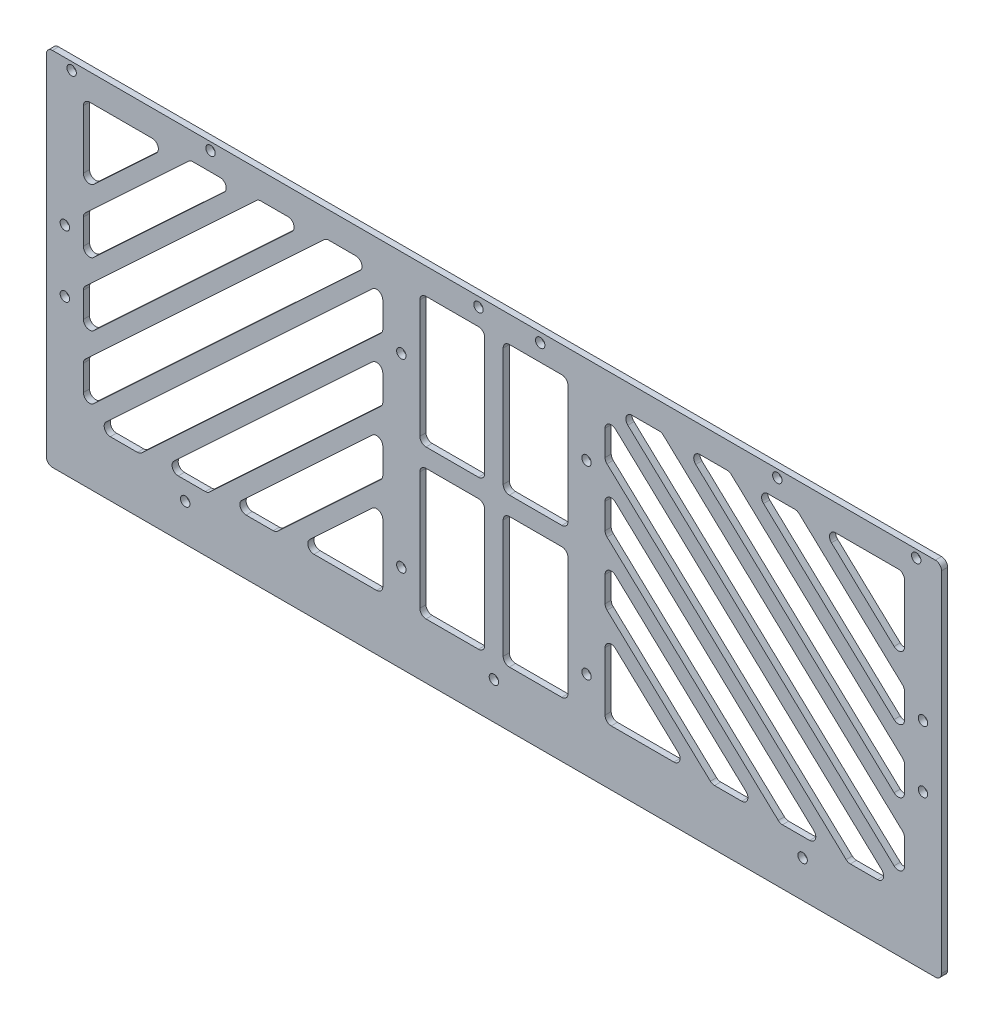
SolidWorks part; units mm, degrees
material "Thornel Mat VMA"
ref_plane "前视基准面" through (0, 0, 0) normal (0, 0, 1) x (1, 0, 0)
ref_plane "上视基准面" through (0, 0, 0) normal (0, 1, 0) x (1, 0, 0)
ref_plane "右视基准面" through (0, 0, 0) normal (1, 0, 0) x (0, 0, -1)
sketch "草图1" plane through (0, 0, 0) normal (0, 0, 1) x (1, 0, 0)
  line L1 (-145, -58.5) -> (145, -58.5)
  line L2 (-145, -58.5) -> (-145, 58.5)
  line L3 (-145, 58.5) -> (145, 58.5)
  line L4 (145, -58.5) -> (145, 58.5)
  line L5 (0, 58.5) -> (0, -58.5) construction
  line L6 (-145, 0) -> (145, 0) construction
  point P0 (0, 0)
  dimension "D1" = 290
  dimension "D2" = 117
extrude "凸台-拉伸1" add sketch "草图1" along normal mid plane 2
sketch "草图2" plane through (0, 0, 1) normal (0, 0, 1) x (1, 0, 0)
  circle A0 centre (136.8, 56) radius 1.25 construction
  circle A1 centre (91.8, 56) radius 1.25 construction
  circle A2 centre (136.8, 56) radius 1.25 construction
  circle A3 centre (91.8, 56) radius 1.25 construction
  circle A4 centre (91.8, 56) radius 1.525
  circle A5 centre (136.8, 56) radius 1.525
  dimension "D1" = 3.05
extrude "切除-拉伸1" cut sketch "草图2" against normal blind 10
mirror "镜向1" about plane through (0, 0, 0) normal (1, 0, 0) of "切除-拉伸1"
sketch "草图3" plane through (0, 0, 1) normal (0, 0, 1) x (1, 0, 0)
  line L0 (-100, -46.5) -> (100, -46.5) construction
  line L1 (0, 0) -> (0, -46.5) construction
  line L2 (-145, -58.5) -> (145, -58.5) construction
  circle A0 centre (-100, -46.5) radius 1.525
  circle A1 centre (0, -46.5) radius 1.525
  circle A2 centre (100, -46.5) radius 1.525
  point P3 (0, -46.5)
  dimension "D3" = 3.05
  dimension "D1" = 12
  dimension "D2" = 200
extrude "切除-拉伸2" cut sketch "草图3" against normal blind 10
sketch "草图4" plane through (0, 0, 1) normal (0, 0, 1) x (1, 0, 0)
  line L0 (0, 0) -> (0, 58.5) construction
  line L1 (145, 58.5) -> (-145, 58.5) construction
  circle A0 centre (-139, -8.5) radius 1.25 construction
  circle A1 centre (-139, 11.5) radius 1.25 construction
  circle A2 centre (-139, -8.5) radius 1.25 construction
  circle A3 centre (-139, 11.5) radius 1.25 construction
  circle A6 centre (-139, 11.5) radius 1.525
  circle A7 centre (-139, -8.5) radius 1.525
  dimension "D1" = 3.05
extrude "切除-拉伸3" cut sketch "草图4" against normal blind 10
mirror "镜向2" about plane through (0, 0, 0) normal (1, 0, 0) of "切除-拉伸3"
fillet "圆角1" radius 2 4 edges at (145, -58.5, 0) (-145, -58.5, 0) (-145, 58.5, 0) (145, 58.5, 0)
sketch "草图5" plane through (0, 0, 1) normal (0, 0, 1) x (1, 0, 0)
  circle A0 centre (15, 55.5) radius 1.25 construction
  circle A1 centre (-5, 55.5) radius 1.25 construction
  circle A2 centre (15, 55.5) radius 1.25 construction
  circle A3 centre (-5, 55.5) radius 1.25 construction
  circle A4 centre (-5, 55.5) radius 1.525
  circle A5 centre (15, 55.5) radius 1.525
  dimension "D1" = 3.05
extrude "切除-拉伸4" cut sketch "草图5" against normal blind 10
sketch "草图6" plane through (0, 0, 1) normal (0, 0, 1) x (1, 0, 0)
  line L1 (-30, -30) -> (30, -30) construction
  line L2 (-30, -30) -> (-30, 30) construction
  line L3 (-30, 30) -> (30, 30) construction
  line L4 (30, -30) -> (30, 30) construction
  line L5 (0, 30) -> (0, -30) construction
  line L6 (-30, 0) -> (30, 0) construction
  circle A0 centre (-30, 30) radius 1.525
  circle A1 centre (-30, -30) radius 1.525
  circle A2 centre (30, -30) radius 1.525
  circle A3 centre (30, 30) radius 1.525
  point P0 (0, 0)
  dimension "D3" = 3.05
  dimension "D1" = 60
  dimension "D2" = 60
extrude "切除-拉伸5" cut sketch "草图6" against normal blind 10
sketch "草图7" plane through (0, 0, 1) normal (0, 0, 1) x (1, 0, 0)
  line L0 (-36, 50) -> (-133, -40.5) construction
  line L1 (-133, 50) -> (-36, 50)
  line L2 (-133, 50) -> (-133, -40.5)
  line L3 (-133, -40.5) -> (-36, -40.5)
  line L4 (-36, 50) -> (-36, -40.5)
  line L5 (-36, 46.5809) -> (-129.3353, -40.5)
  line L6 (-36, 32.9044) -> (-114.6765, -40.5)
  line L7 (0, 0) -> (0, 58.5) construction
  line L8 (-36, 12.3896) -> (-92.6883, -40.5)
  line L9 (-36, 26.0661) -> (-107.3471, -40.5)
  line L10 (-36, -8.1252) -> (-70.7001, -40.5)
  line L11 (-36, 5.5513) -> (-85.3589, -40.5)
  line L12 (-39.4109, 50.2368) -> (-133, -37.0809)
  line L13 (-36, -14.9634) -> (-63.3707, -40.5)
  line L14 (-5.3017, 0.0012) -> (-83.9782, -73.4031) [skipped]
  line L15 (-54.3235, 50) -> (-133, -23.4044)
  line L16 (-61.6529, 50) -> (-133, -16.5661)
  line L17 (-76.3117, 50) -> (-133, -2.8896)
  line L18 (-83.6411, 50) -> (-133, 3.9487)
  line L19 (-98.2999, 50) -> (-133, 17.6252)
  line L20 (-105.6293, 50) -> (-133, 24.4634)
  line L21 (143, 58.5) -> (-143, 58.5) construction
  line L22 (36, 50) -> (133, -40.5) construction
  line L23 (105.6293, 50) -> (133, 24.4634)
  line L24 (98.2999, 50) -> (133, 17.6252)
  line L25 (83.6411, 50) -> (133, 3.9487)
  line L26 (76.3117, 50) -> (133, -2.8896)
  line L27 (61.6529, 50) -> (133, -16.5661)
  line L28 (54.3235, 50) -> (133, -23.4044)
  line L29 (36, -14.9634) -> (63.3707, -40.5)
  line L30 (39.4109, 50.2368) -> (133, -37.0809)
  line L31 (36, 5.5513) -> (85.3589, -40.5)
  line L32 (36, -8.1252) -> (70.7001, -40.5)
  line L33 (36, 26.0661) -> (107.3471, -40.5)
  line L34 (36, 12.3896) -> (92.6883, -40.5)
  line L35 (36, 32.9044) -> (114.6765, -40.5)
  line L36 (36, 46.5809) -> (129.3353, -40.5)
  line L37 (36, 50) -> (36, -40.5)
  line L38 (133, -40.5) -> (36, -40.5)
  line L39 (133, 50) -> (133, -40.5)
  line L40 (133, 50) -> (36, 50)
  circle A0 centre (-100, -46.5) radius 1.525 construction
  circle A1 centre (-139, -8.5) radius 1.525 construction
  circle A2 centre (-91.8, 56) radius 1.525 construction
  circle A3 centre (-30, 30) radius 1.525 construction
  point P42 (-104.6559, 23.5552)
  dimension "D2" = 6
  dimension "D1" = 6
  dimension "D3" = 6
  dimension "D4" = 6
  dimension "D5" = 2.5
  dimension "D6" = 10
  dimension "D8" = 15
  dimension "D9" = 10
  dimension "D10" = 5
  dimension "D11" = 10
  dimension "D12" = 5
  dimension "D13" = 10
  dimension "D14" = 5
  dimension "D7" = 4
extrude "切除-拉伸6" cut sketch "草图7" against normal blind 10 contours L4 L13 L3 | L4 L11 L3 L10 | L4 L9 L3 L8 | L6 L4 L5 L3 | L1 L15 L2 L12 | L1 L17 L2 L16 | L1 L19 L2 L18 | L20 L1 L2 | L38 L29 L37 | L38 L31 L37 L32 | L38 L33 L37 L34 | L38 L36 L37 L35 | L28 L40 L30 L39 | L26 L40 L27 L39 | L24 L40 L25 L39 | L39 L40 L23
sketch "草图8" plane through (0, 0, 1) normal (0, 0, 1) x (1, 0, 0)
  line L0 (-54.3235, 50) -> (-39.6647, 50) construction
  line L1 (-24, 50) -> (24, 50)
  line L2 (-24, 50) -> (-24, -40.5)
  line L3 (-24, -40.5) -> (24, -40.5)
  line L4 (24, 50) -> (24, -40.5)
  line L5 (63.3707, -40.5) -> (36, -40.5) construction
  line L6 (0, 50) -> (0, -40.5) construction
  line L7 (-24, 4.75) -> (24, 4.75) construction
  line L8 (-3, 50) -> (-3, -40.5)
  line L9 (-24, 1.75) -> (24, 1.75)
  line L10 (3, 50) -> (3, -40.5)
  line L11 (-24, 7.75) -> (24, 7.75)
  circle A0 centre (30, 30) radius 1.525 construction
  circle A1 centre (-30, 30) radius 1.525 construction
  dimension "D1" = 6
  dimension "D2" = 6
  dimension "D3" = 3
  dimension "D4" = 3
extrude "切除-拉伸7" cut sketch "草图8" against normal blind 10 contours L9 L2 L3 L8 | L9 L10 L3 L4 | L10 L11 L4 L1 | L2 L11 L8 L1
fillet "圆角2" radius 2 76 edges at (24, -40.5, 0) (3, -40.5, 0) (3, 1.75, 0) (24, 1.75, 0) (-3, -40.5, 0) (-24, 1.75, 0) (-3, 1.75, 0) (-133, 3.9487, 0) (-133, 17.6252, 0) (-98.2999, 50, 0) (-83.6411, 50, 0) (-133, -16.5661, 0) (-133, -2.8896, 0) (-76.3117, 50, 0) (-61.6529, 50, 0) (-133, 50, 0) (-105.6293, 50, 0) (-133, 24.4634, 0) (36, -14.9634, 0) (63.3707, -40.5, 0) (36, -40.5, 0) (-92.6883, -40.5, 0) (-107.3471, -40.5, 0) (-36, 26.0661, 0) (-36, 12.3896, 0) (-70.7001, -40.5, 0) (-85.3589, -40.5, 0) (-36, 5.5513, 0) (-36, -8.1252, 0) (-133, -37.0809, 0) (-133, -23.4044, 0) (-54.3235, 50, 0) (-39.6647, 50, 0) (-129.3353, -40.5, 0) (-36, 46.5809, 0) (-36, 32.9044, 0) (-114.6765, -40.5, 0) (133, 3.9487, 0) (83.6411, 50, 0) (98.2999, 50, 0) (133, 17.6252, 0) (133, -16.5661, 0) (61.6529, 50, 0) (76.3117, 50, 0) (133, -2.8896, 0) (105.6293, 50, 0) (133, 50, 0) (133, 24.4634, 0) (36, 12.3896, 0) (36, 26.0661, 0) (107.3471, -40.5, 0) (92.6883, -40.5, 0) (36, -8.1252, 0) (36, 5.5513, 0) (85.3589, -40.5, 0) (70.7001, -40.5, 0) (133, -37.0809, 0) (39.6647, 50, 0) (54.3235, 50, 0) (133, -23.4044, 0) (36, 32.9044, 0) (36, 46.5809, 0) (129.3353, -40.5, 0) (114.6765, -40.5, 0) (-63.3707, -40.5, 0) (-36, -14.9634, 0) (3, 50, 0) (24, 50, 0) (24, 7.75, 0) (3, 7.75, 0) (-24, 50, 0) (-3, 50, 0) (-3, 7.75, 0) (-24, 7.75, 0) (-24, -40.5, 0) (-36, -40.5, 0)
